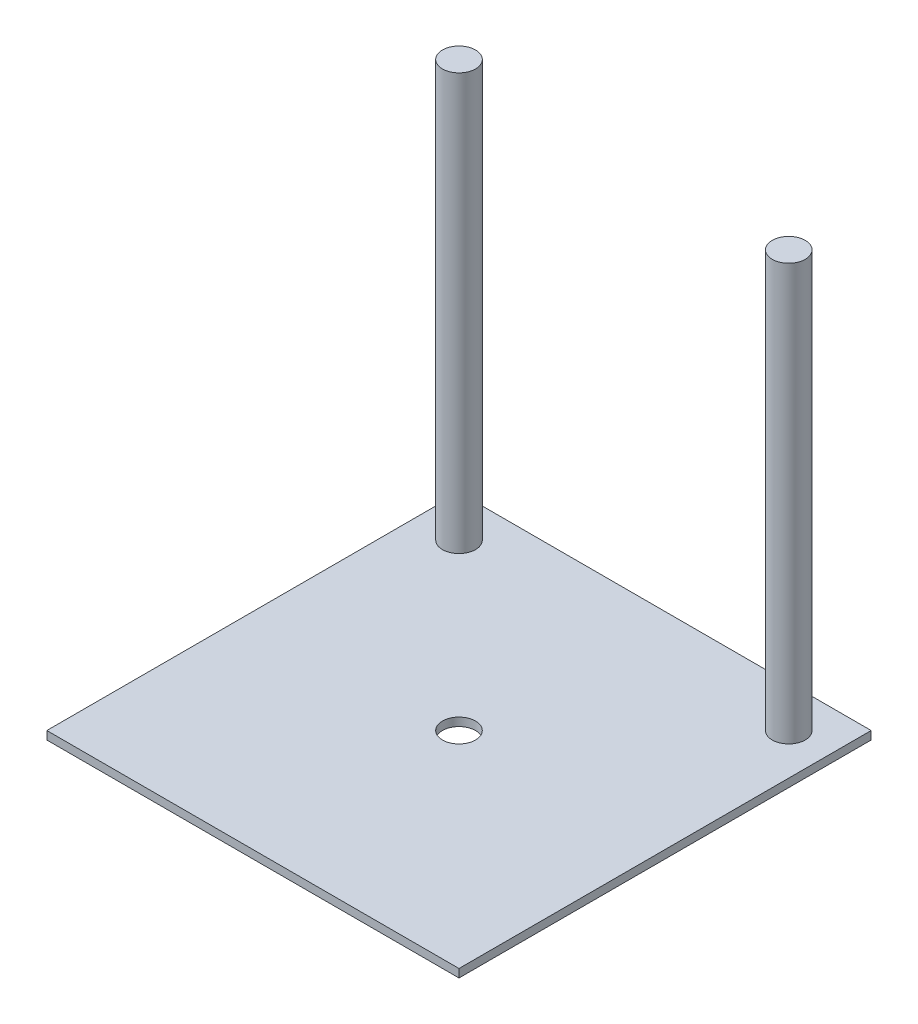
SolidWorks part; units mm, degrees
ref_plane "Front Plane" through (0, 0, 0) normal (0, 0, 1) x (1, 0, 0)
ref_plane "Top Plane" through (0, 0, 0) normal (0, 1, 0) x (1, 0, 0)
ref_plane "Right Plane" through (0, 0, 0) normal (1, 0, 0) x (0, 0, -1)
sketch "Sketch1" plane through (0, 0, 0) normal (0, 1, 0) x (1, 0, 0)
  line L1 (0, 0) -> (50, 0)
  line L2 (0, 0) -> (0, 50)
  line L3 (0, 50) -> (50, 50)
  line L4 (50, 0) -> (50, 50)
  circle A0 centre (25, 25) radius 2
extrude "Boss-Extrude1" add sketch "Sketch1" along normal blind 1
sketch "Sketch2" plane through (0, 1, 0) normal (0, 1, 0) x (1, 0, 0)
  circle A0 centre (5, 45) radius 2
  circle A1 centre (45, 45) radius 2
extrude "Boss-Extrude2" add sketch "Sketch2" along normal blind 70
sketch "Sketch7" plane through (0, 71, 0) normal (0, 1, 0) x (1, 0, 0)
  circle A0 centre (5, 45) radius 2
  circle A1 centre (45, 45) radius 2
extrude "Cut-Extrude1" cut sketch "Sketch7" against normal blind 9.5
sketch "Sketch9" plane through (0, 61.5, 0) normal (0, 1, 0) x (1, 0, 0)
  circle A0 centre (5, 45) radius 2
  circle A1 centre (45, 45) radius 2
extrude "Cut-Extrude2" cut sketch "Sketch9" against normal blind 10
